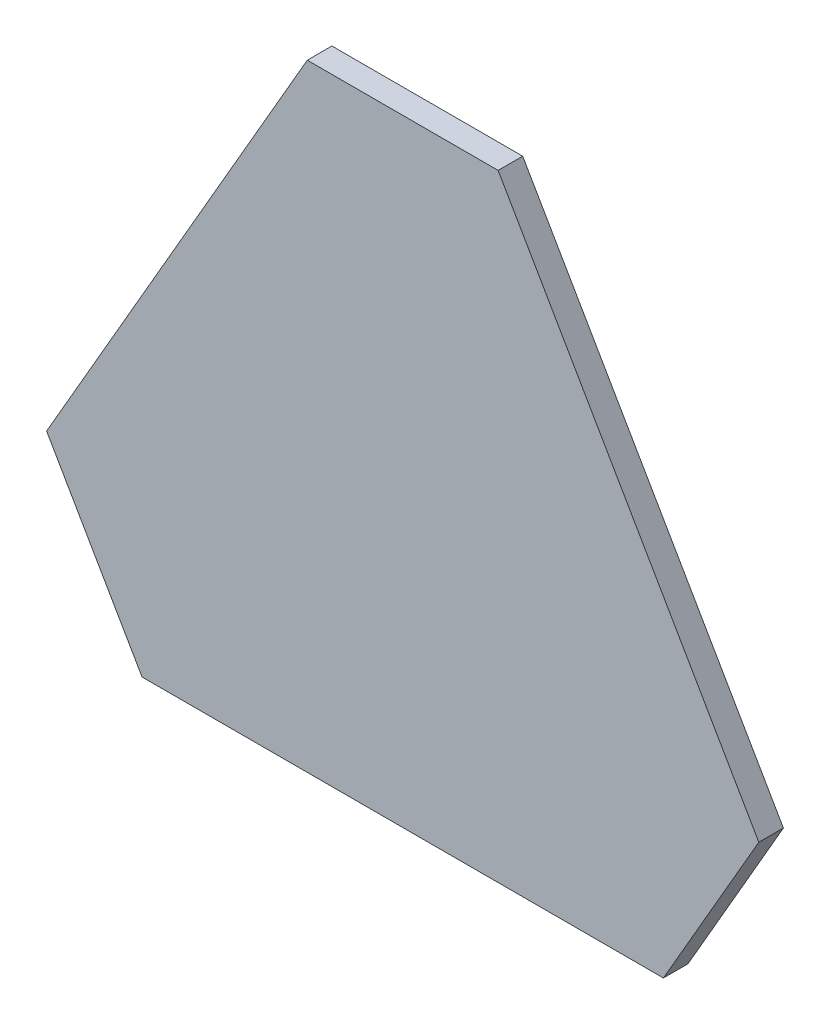
SolidWorks part; units mm, degrees
ref_plane "Front Plane" through (0, 0, 0) normal (0, 0, 1) x (1, 0, 0)
ref_plane "Top Plane" through (0, 0, 0) normal (0, 1, 0) x (1, 0, 0)
ref_plane "Right Plane" through (0, 0, 0) normal (1, 0, 0) x (0, 0, -1)
sketch "Sketch1" plane through (0, 0, 0) normal (0, 0, -1) x (1, 0, 0)
  line L0 (1448.8887, 388.2286) -> (388.2286, -1448.8887)
  line L1 (388.2286, -1448.8887) -> (-388.2286, -1448.8887)
  line L2 (-388.2286, -1448.8887) -> (-1448.8887, 388.2286)
  line L3 (-1448.8887, 388.2286) -> (-1060.6602, 1060.6602)
  line L4 (-1060.6602, 1060.6602) -> (1060.6602, 1060.6602)
  line L5 (1060.6602, 1060.6602) -> (1448.8887, 388.2286)
  line L6 (1060.6602, 1060.6602) -> (0, 0) construction
  line L7 (0, 0) -> (1448.8887, 388.2286) construction
  line L8 (0, 0) -> (-1060.6602, 1060.6602) construction
  line L9 (0, 0) -> (-1448.8887, 388.2286) construction
  line L10 (388.2286, -1448.8887) -> (0, 0) construction
  line L11 (0, 0) -> (-388.2286, -1448.8887) construction
  dimension "D1" = 1500
  dimension "D2" = 30
  dimension "D3" = 1500
  dimension "D4" = 1500
  dimension "D5" = 1500
  dimension "D6" = 30
  dimension "D7" = 30
  dimension "D8" = 1500
  dimension "D9" = 1500
  dimension "D10" = 90
extrude "Boss-Extrude1" add sketch "Sketch1" along normal blind 100
